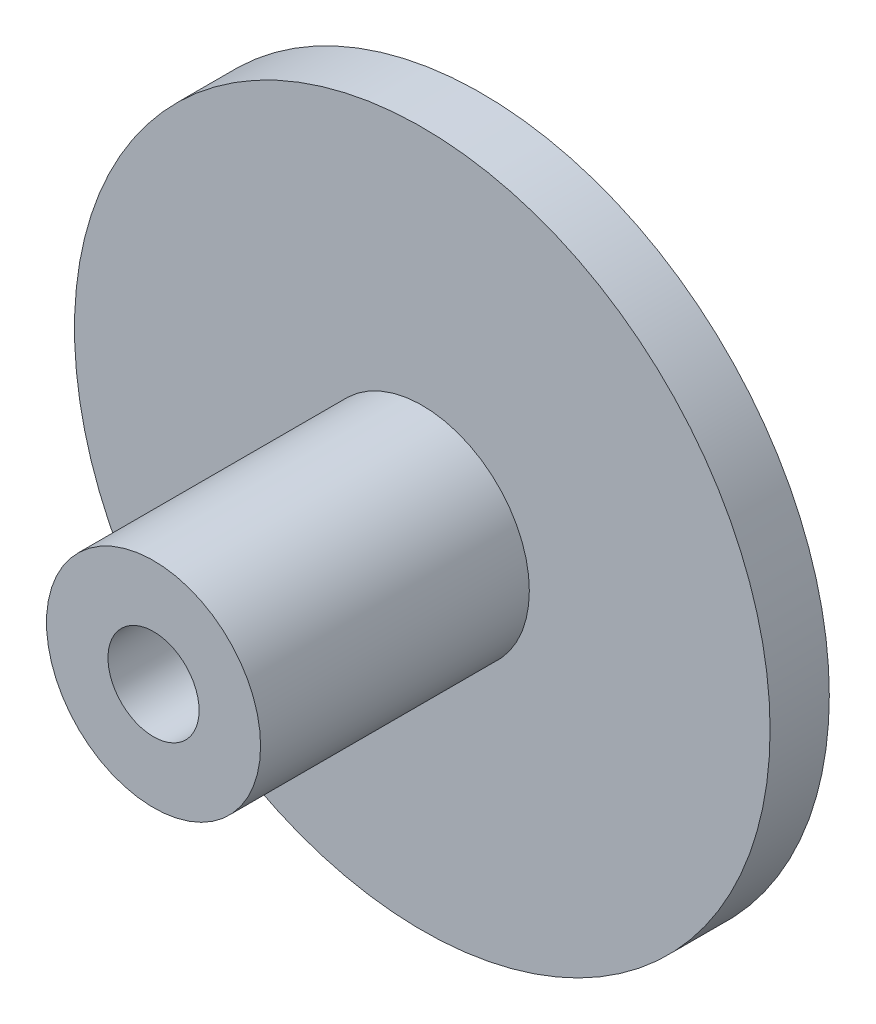
SolidWorks part; units mm, degrees
ref_plane "前视基准面" through (0, 0, 0) normal (0, 0, 1) x (1, 0, 0)
ref_plane "上视基准面" through (0, 0, 0) normal (0, 1, 0) x (1, 0, 0)
ref_plane "右视基准面" through (0, 0, 0) normal (1, 0, 0) x (0, 0, -1)
sketch "草图1" plane through (0, 0, 0) normal (0, 0, 1) x (1, 0, 0)
  circle A0 centre (0, 0) radius 7.635
  circle A1 centre (0, 0) radius 1
  dimension "D1" = 15.27
  dimension "D2" = 2
extrude "凸台-拉伸1" add sketch "草图1" along normal blind 1.3
sketch "草图2" plane through (0, 0, 1.3) normal (0, 0, 1) x (1, 0, 0)
  circle A0 centre (0, 0) radius 2.35
  circle A1 centre (0, 0) radius 1 construction
  circle A2 centre (0, 0) radius 1
  dimension "D1" = 4.7
extrude "凸台-拉伸2" add sketch "草图2" along normal blind 5.9
